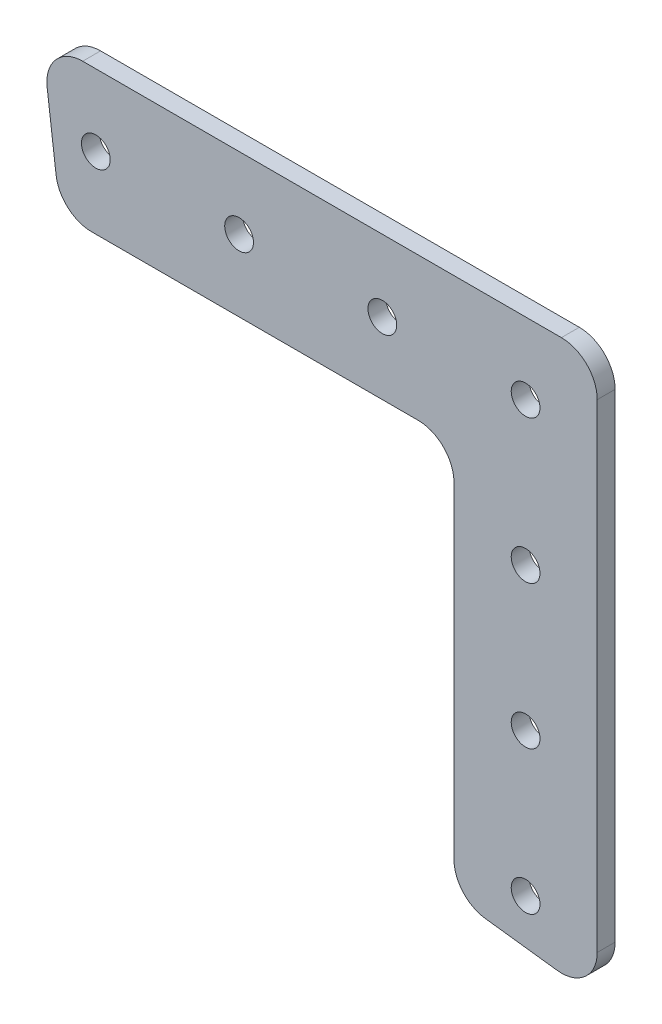
SolidWorks part; units mm, degrees
material "6061-T6 (SS)"
ref_plane "Front" through (0, 0, 0) normal (0, 0, 1) x (1, 0, 0)
ref_plane "Top" through (0, 0, 0) normal (0, 1, 0) x (1, 0, 0)
ref_plane "Right" through (0, 0, 0) normal (1, 0, 0) x (0, 0, -1)
sketch "Sketch1" plane through (0, 0, 0) normal (0, 0, 1) x (1, 0, 0)
  line L0 (-12.7, 247.65) -> (-12.7, 317.5)
  line L3 (-12.7, 317.5) -> (-82.55, 317.5)
  line L8 (-57.1338, 261.3851) -> (-30.9289, 252.5188)
  line L9 (-25.4, 249.2375) -> (5.5624, 245.3672)
  line L10 (12.7, 251.6682) -> (12.7, 336.55)
  line L11 (6.35, 342.9) -> (-78.5318, 342.9)
  line L12 (-84.8328, 335.7624) -> (-80.9625, 304.8)
  line L13 (-77.6812, 299.2711) -> (-68.8149, 273.0662)
  line L15 (-12.7, 247.65) -> (5.5624, 245.3672)
  line L16 (12.7, 251.6682) -> (12.7, 336.55)
  line L17 (6.35, 342.9) -> (-78.5318, 342.9)
  line L18 (-84.8328, 335.7624) -> (-82.55, 317.5)
  arc A10 (-60.6145, 264.2539) -> (-65.9461, 269.5855) centre (-73.025, 257.175) ccw
  arc A11 (-60.6145, 264.2539) -> (-57.1338, 261.3851) centre (-55.0987, 267.4001) ccw
  arc A12 (-29.3279, 251.3068) -> (-30.9289, 252.5188) centre (-31.9464, 249.5113) ccw
  arc A13 (-29.3279, 251.3068) -> (-25.4, 249.2375) centre (-25.4, 254) ccw
  arc A14 (5.5624, 245.3672) -> (12.7, 251.6682) centre (6.35, 251.6682) ccw
  arc A15 (12.7, 336.55) -> (6.35, 342.9) centre (6.35, 336.55) ccw
  arc A16 (-78.5318, 342.9) -> (-84.8328, 335.7624) centre (-78.5318, 336.55) ccw
  arc A17 (-80.9625, 304.8) -> (-78.8932, 300.8721) centre (-76.2, 304.8) ccw
  arc A18 (-77.6812, 299.2711) -> (-78.8932, 300.8721) centre (-80.6887, 298.2536) ccw
  arc A19 (-68.8149, 273.0662) -> (-65.9461, 269.5855) centre (-62.7999, 275.1013) ccw
  arc A24 (5.5624, 245.3672) -> (12.7, 251.6682) centre (6.35, 251.6682) ccw
  arc A25 (12.7, 336.55) -> (6.35, 342.9) centre (6.35, 336.55) ccw
  arc A26 (-78.5318, 342.9) -> (-84.8328, 335.7624) centre (-78.5318, 336.55) ccw
  dimension "D1" = 0
extrude "Boss-Extrude1" add sketch "Sketch1" along normal blind 3.175
fillet "Fillet1" radius 6.35 3 edges at (-82.55, 317.5, 1.5875) (-12.7, 317.5, 1.5875) (-12.7, 247.65, 1.5875)
hole_wizard "#10 Clearance Hole1" positions "Sketch2" profile "Sketch3" hole size "#10" standard "ANSI Inch"
sketch "Sketch2" plane through (0, 0, 0) normal (0, 0, -1) x (-1, 0, 0)
  arc A0 (0, 256.0193) -> (0, 251.9807) centre (0, 254) ccw construction
  arc A1 (0, 281.4193) -> (0, 277.3807) centre (0, 279.4) ccw construction
  arc A2 (76.2, 332.2193) -> (76.2, 328.1807) centre (76.2, 330.2) ccw construction
  arc A3 (50.8, 332.2193) -> (50.8, 328.1807) centre (50.8, 330.2) ccw construction
  point P0 (0, 330.2)
  point P3 (0, 304.8)
  point P6 (0, 279.4)
  point P8 (25.4, 330.2)
  point P11 (0, 254)
  point P31 (50.8, 330.2)
  point P33 (76.2, 330.2)
  point P36 (0, 0)
  point P42 (0, 0)
  point P46 (0, 0)
sketch "Sketch3" plane through (0, 330.2, 0) normal (1, 0, 0) x (0, 1, 0)
  line L0 (0, 0) -> (0, 11.4398)
  line L1 (0, 11.4398) -> (2.5527, 9.906)
  line L2 (2.5527, 9.906) -> (2.5527, 0)
  line L5 (2.5527, 0) -> (0, 0)
  line L10 (0, 11.4398) -> (-2.5527, 9.906) construction
  line L11 (0, -6.35) -> (0, 107.95) construction
  dimension "Hole Dia." = 5.1054
  dimension "Hole Depth" = 9.906
  dimension "Drill Angle" = 118
